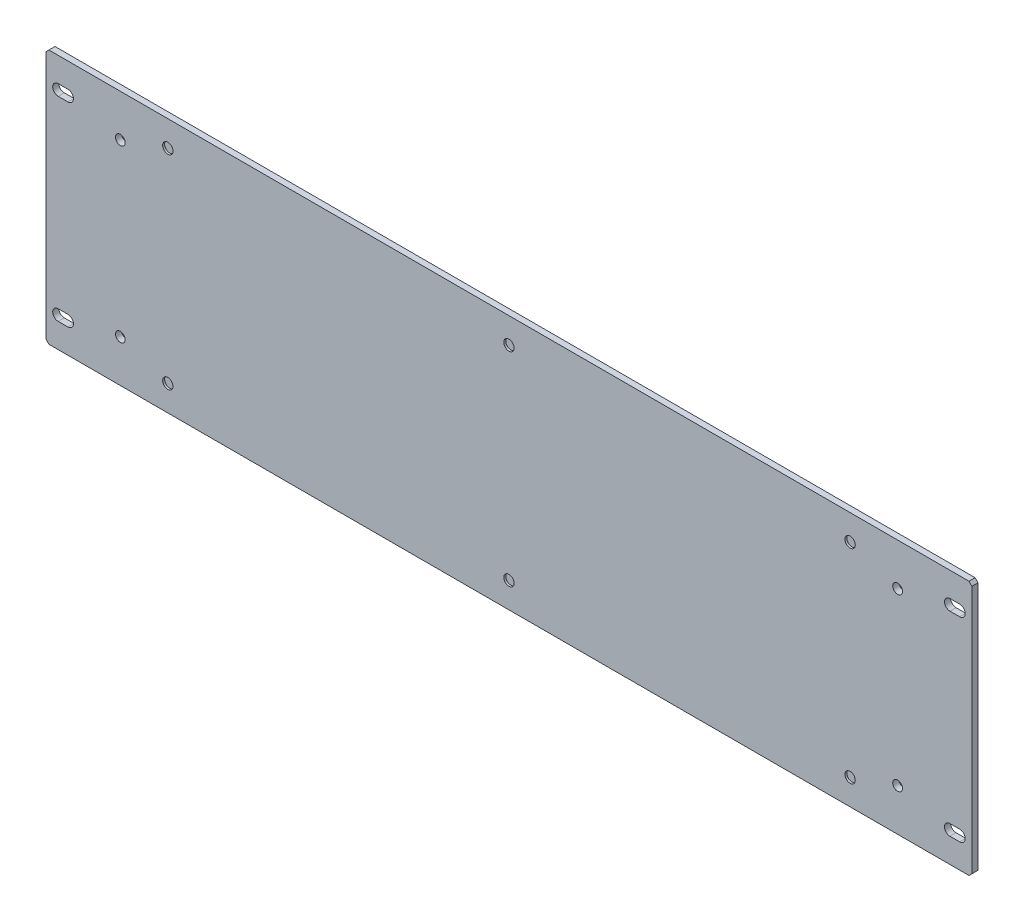
SolidWorks part; units mm, degrees
material "Ductile Iron"
ref_plane "Front Plane" through (0, 0, 0) normal (0, 0, 1) x (1, 0, 0)
ref_plane "Top Plane" through (0, 0, 0) normal (0, 1, 0) x (1, 0, 0)
ref_plane "Right Plane" through (0, 0, 0) normal (1, 0, 0) x (0, 0, -1)
sketch "Sketch1" plane through (0, 0, 0) normal (0, 0, 1) x (1, 0, 0)
  line L0 (-57.2704, -1.8182) -> (-52.1904, -1.8182) construction
  line L1 (-63.6204, 13.8028) -> (418.9796, 13.8028)
  line L2 (-63.6204, 13.8028) -> (-63.6204, -119.0392)
  line L3 (-63.6204, -119.0392) -> (418.9796, -119.0392)
  line L4 (418.9796, 13.8028) -> (418.9796, -119.0392)
  line L5 (-57.2704, 1.0393) -> (-52.1904, 1.0393)
  line L6 (-57.2704, -4.6757) -> (-52.1904, -4.6757)
  line L7 (407.5496, -1.8182) -> (412.6296, -1.8182) construction
  line L8 (407.5496, 1.0393) -> (412.6296, 1.0393)
  line L9 (407.5496, -4.6757) -> (412.6296, -4.6757)
  line L10 (-57.2704, -103.4182) -> (-52.1904, -103.4182) construction
  line L11 (-57.2704, -100.5607) -> (-52.1904, -100.5607)
  line L12 (-57.2704, -106.2757) -> (-52.1904, -106.2757)
  line L13 (407.5496, -103.4182) -> (412.6296, -103.4182) construction
  line L14 (407.5496, -100.5607) -> (412.6296, -100.5607)
  line L15 (407.5496, -106.2757) -> (412.6296, -106.2757)
  circle A0 centre (-24.8854, -8.1682) radius 2.54
  circle A1 centre (-24.8854, -97.0682) radius 2.54
  circle A2 centre (380.2446, -97.0682) radius 2.54
  circle A3 centre (380.2446, -8.1682) radius 2.54
  arc A4 (-57.2704, 1.0393) -> (-57.2704, -4.6757) centre (-57.2704, -1.8182) ccw
  arc A5 (-52.1904, -4.6757) -> (-52.1904, 1.0393) centre (-52.1904, -1.8182) ccw
  arc A6 (407.5496, 1.0393) -> (407.5496, -4.6757) centre (407.5496, -1.8182) ccw
  arc A7 (412.6296, -4.6757) -> (412.6296, 1.0393) centre (412.6296, -1.8182) ccw
  arc A8 (-57.2704, -100.5607) -> (-57.2704, -106.2757) centre (-57.2704, -103.4182) ccw
  arc A9 (-52.1904, -106.2757) -> (-52.1904, -100.5607) centre (-52.1904, -103.4182) ccw
  arc A10 (407.5496, -100.5607) -> (407.5496, -106.2757) centre (407.5496, -103.4182) ccw
  arc A11 (412.6296, -106.2757) -> (412.6296, -100.5607) centre (412.6296, -103.4182) ccw
  point P14 (-54.7304, -1.8182)
  point P23 (410.0896, -1.8182)
  point P30 (-54.7304, -103.4182)
  point P37 (410.0896, -103.4182)
  dimension "D3" = 5.08
  dimension "D4" = 5.08
  dimension "D5" = 2
  dimension "D6" = 5.08
  dimension "D18" = 2.8575
  dimension "D8" = 21.971
  dimension "D10" = 15.621
  dimension "D11" = 405.13
  dimension "D9" = 38.735
  dimension "D15" = 88.9
  dimension "D1" = 482.6
  dimension "D2" = 132.842
  dimension "D7" = 38.735
  dimension "D12" = 8.89
  dimension "D14" = 8.89
  dimension "D16" = 2
  dimension "D13" = 2
extrude "Boss-Extrude1" add sketch "Sketch1" along normal blind 3.175
sketch "Sketch2" plane through (0, 0, 3.175) normal (0, 0, 1) x (1, 0, 0)
  line L0 (418.9796, 13.8028) -> (-63.6204, 13.8028) construction
  line L1 (-19.8054, 9.6118) -> (375.1646, 9.6118)
  line L2 (-19.8054, 9.6118) -> (-19.8054, 8.0878)
  line L3 (-19.8054, 8.0878) -> (375.1646, 8.0878)
  line L4 (375.1646, 9.6118) -> (375.1646, 8.0878)
  line L5 (-63.6204, 13.8028) -> (-63.6204, -119.0392) construction
  line L6 (418.9796, -119.0392) -> (418.9796, 13.8028) construction
  line L9 (-19.8054, -25.9482) -> (-19.8054, -24.4242)
  line L10 (375.1646, -25.9482) -> (375.1646, -24.4242)
  line L11 (-19.8054, -24.4242) -> (375.1646, -24.4242)
  line L12 (-19.8054, -25.9482) -> (375.1646, -25.9482)
  dimension "D1" = 4.191
  dimension "D2" = 1.524
  dimension "D3" = 43.815
  dimension "D4" = 43.815
  dimension "D5" = 35.56
  dimension "D6" = 43.815
  dimension "D7" = 43.815
  dimension "D8" = 1.524
extrude "Boss-Extrude2" [suppressed] add sketch "Sketch2" along normal blind 10.16
sketch "Sketch3" [suppressed] plane through (0, 98.5118, 0) normal (0, 1, 0) x (-1, 0, 0)
  line L0 (61.8424, 3.175) -> (61.8424, 0) construction
  line L2 (-376.9426, 3.175) -> (18.0274, 3.175) construction
  circle A0 centre (11.0424, 10.795) radius 1.27
  circle A1 centre (-115.9576, 10.795) radius 1.27
  circle A2 centre (-242.9576, 10.795) radius 1.27
  circle A3 centre (-369.9576, 10.795) radius 1.27
  dimension "D1" = 2.54
  dimension "D4" = 7.62
  dimension "D2" = 50.8
  dimension "D3" = 4
extrude "Cut-Extrude1" [suppressed] cut sketch "Sketch3" against normal through all
sketch "Sketch5" plane through (0, 0, 3.175) normal (0, 0, 1) x (1, 0, 0)
  line L1 (-63.6204, 13.8028) -> (-63.6204, -119.0392) construction
  line L3 (418.9796, 13.8028) -> (-63.6204, 13.8028) construction
  circle A0 centre (-0.1204, 0.4678) radius 2.7051
  circle A1 centre (177.6796, 0.4678) radius 2.7051
  circle A2 centre (355.4796, 0.4678) radius 2.7051
  circle A3 centre (177.6796, -105.7042) radius 2.7051
  circle A4 centre (355.4796, -105.7042) radius 2.7051
  circle A5 centre (-0.1204, -105.7042) radius 2.7051
  dimension "D1" = 5.4102
  dimension "D2" = 106.172
  dimension "D3" = 63.5
  dimension "D6" = 13.335
  dimension "D7" = 177.8
  dimension "D4" = 3
  dimension "D5" = 2
extrude "Cut-Extrude2" cut sketch "Sketch5" against normal blind 1.0414
chamfer "Chamfer1" distance 1.524 angle 45 4 edges at (-63.6204, -119.0392, 1.5875) (418.9796, -119.0392, 1.5875) (418.9796, 13.8028, 1.5875) (-63.6204, 13.8028, 1.5875)
